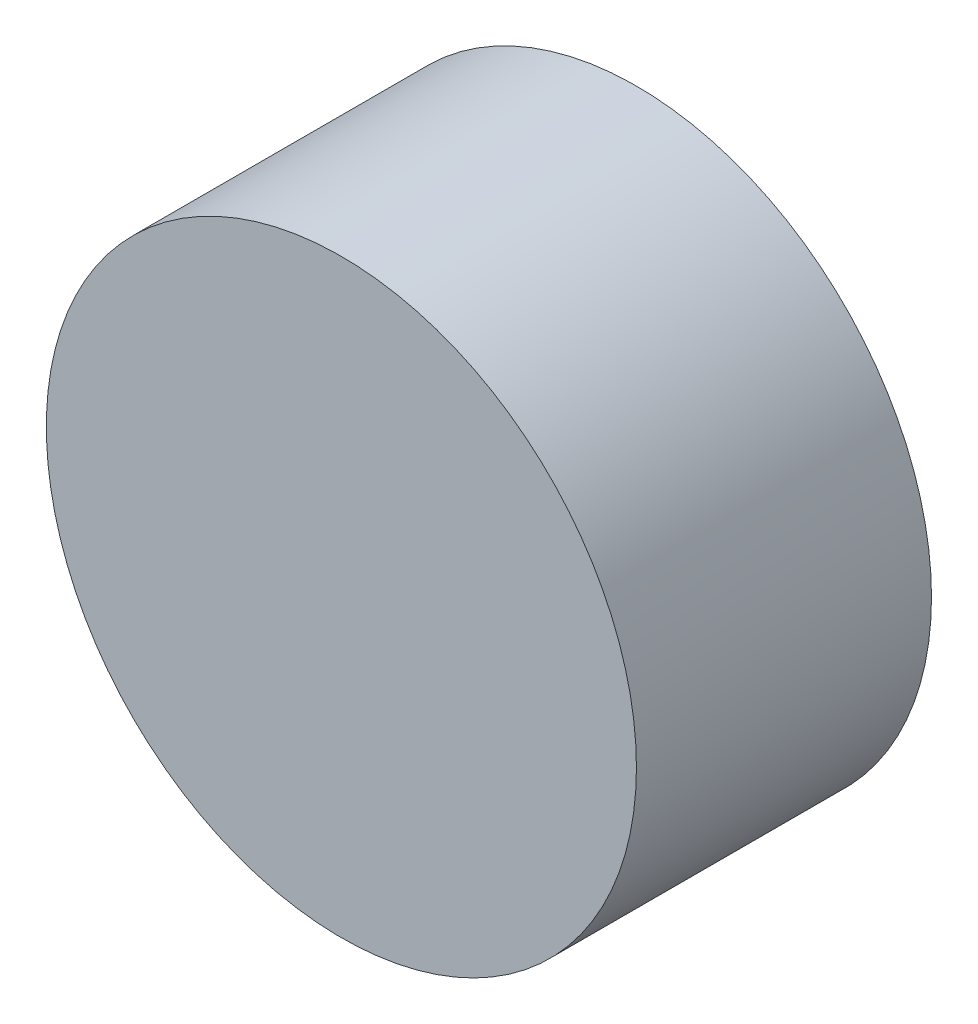
SolidWorks part; units mm, degrees
ref_plane "正面" through (0, 0, 0) normal (0, 0, 1) x (1, 0, 0)
ref_plane "平面" through (0, 0, 0) normal (0, 1, 0) x (1, 0, 0)
ref_plane "右側面" through (0, 0, 0) normal (1, 0, 0) x (0, 0, -1)
sketch "ｽｹｯﾁ1" plane through (0, 0, 0) normal (0, 0, 1) x (1, 0, 0)
  circle A0 centre (0, 0) radius 10
extrude "ﾎﾞｽ - 押し出し1" add sketch "ｽｹｯﾁ1" along normal blind 10
